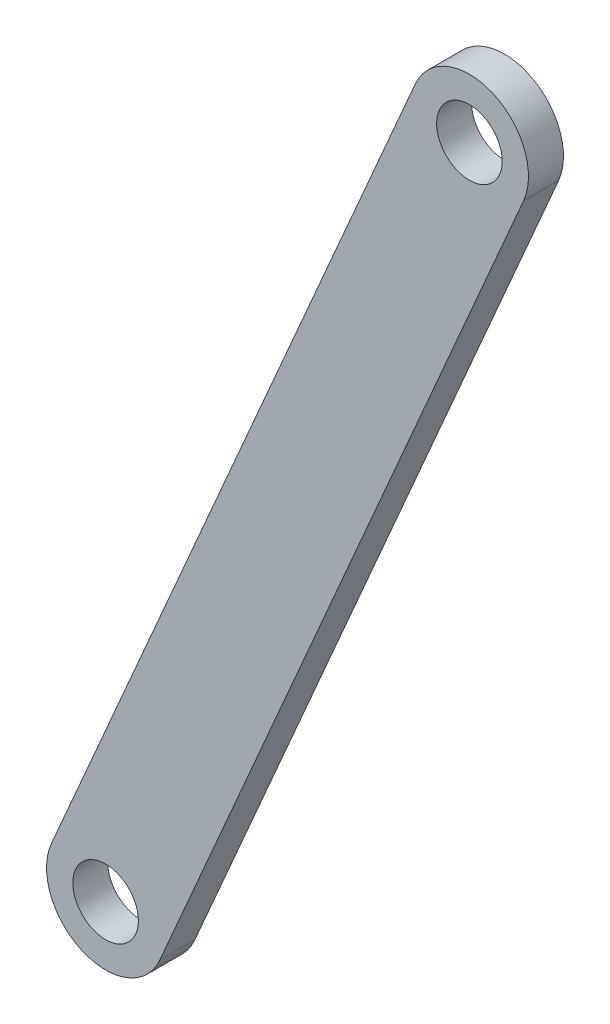
SolidWorks part; units mm, degrees
material "1023 Carbon Steel Sheet (SS)"
ref_plane "Front Plane" through (0, 0, 0) normal (0, 0, 1) x (1, 0, 0)
ref_plane "Top Plane" through (0, 0, 0) normal (0, 1, 0) x (1, 0, 0)
ref_plane "Right Plane" through (0, 0, 0) normal (1, 0, 0) x (0, 0, -1)
sketch "Sketch1" plane through (0, 0, 0) normal (0, 0, 1) x (1, 0, 0)
  line L0 (0, 0) -> (520, 1200) construction
  line L1 (-77.4188, 33.5481) -> (442.5812, 1233.5481)
  line L2 (77.4188, -33.5481) -> (597.4188, 1166.4519)
  arc A0 (-77.4188, 33.5481) -> (77.4188, -33.5481) centre (0, 0) ccw
  arc A1 (597.4188, 1166.4519) -> (442.5812, 1233.5481) centre (520, 1200) ccw
  circle A2 centre (520, 1200) radius 46.875
  circle A3 centre (0, 0) radius 46.875
  point P3 (260, 600)
  dimension "D3" = 84.375
  dimension "D4" = 93.75
  dimension "D1" = 520
  dimension "D2" = 1200
extrude "Boss-Extrude1" add sketch "Sketch1" along normal blind 50
